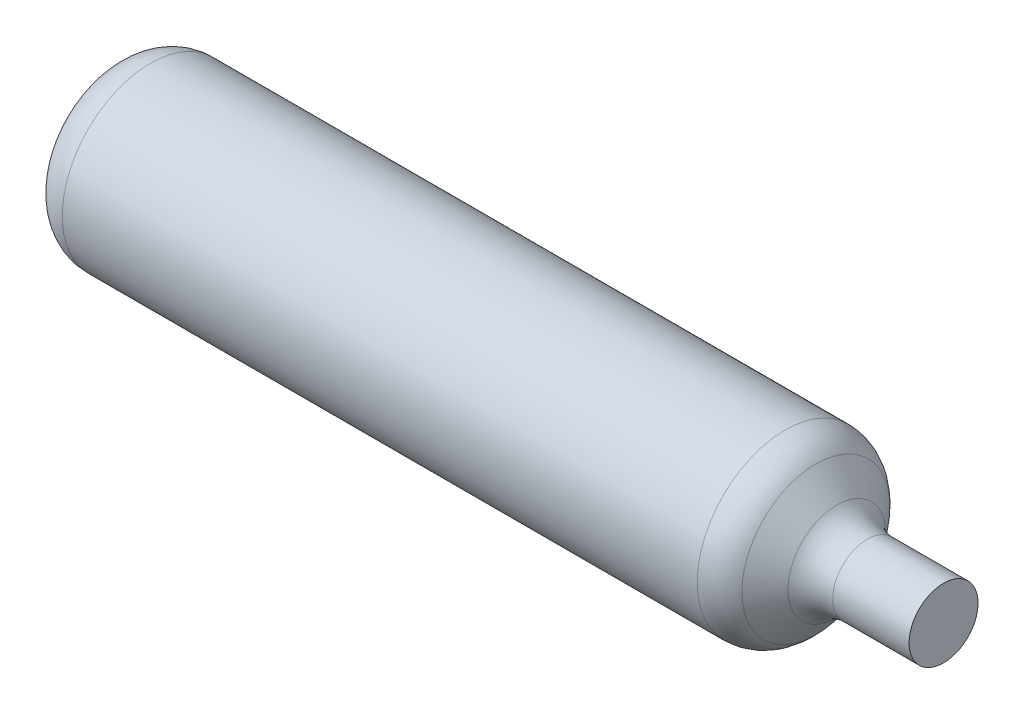
SolidWorks part; units mm, degrees
ref_plane "Front Plane" through (0, 0, 0) normal (0, 0, 1) x (1, 0, 0)
ref_plane "Top Plane" through (0, 0, 0) normal (0, 1, 0) x (1, 0, 0)
ref_plane "Right Plane" through (0, 0, 0) normal (1, 0, 0) x (0, 0, -1)
sketch "Skica1" plane through (0, 0, 0) normal (0, 0, 1) x (1, 0, 0)
  line L0 (0, 0) -> (174.7196, 0) construction
  line L1 (0, 0) -> (0, 44.5)
  line L2 (0, 44.5) -> (349.5995, 44.5)
  line L3 (349.5995, 44.5) -> (372.1348, 17.4006)
  line L4 (372.1348, 17.4006) -> (420, 17.4006)
  line L5 (420, 17.4006) -> (420, 0)
  line L6 (420, 0) -> (0, 0)
  dimension "D1" = 89
  dimension "D2" = 420
revolve "Rotovat1" add sketch "Skica1" angle 360 about L0
fillet "Zaoblit1" radius 20 3 edges at (372.1348, 0, 17.4006) (349.5995, 0, 44.5) (0, 0, 44.5)
